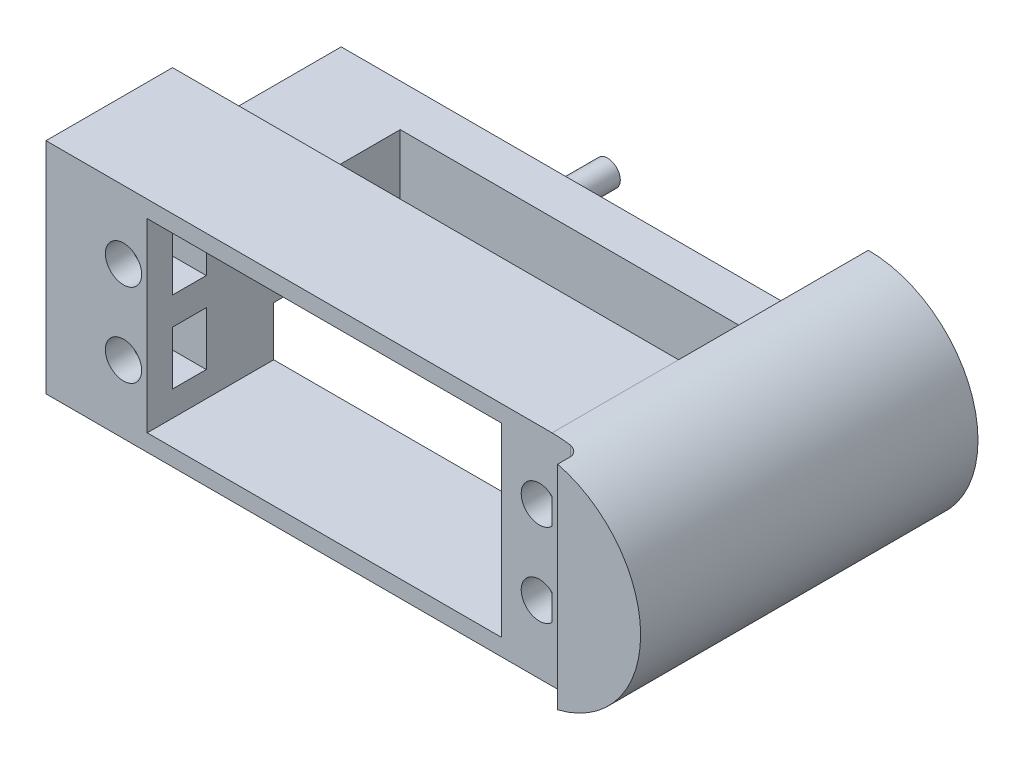
SolidWorks part; units mm, degrees
ref_plane "Plan de face" through (0, 0, 0) normal (0, 0, 1) x (1, 0, 0)
ref_plane "Plan de dessus" through (0, 0, 0) normal (0, 1, 0) x (1, 0, 0)
ref_plane "Plan de droite" through (0, 0, 0) normal (1, 0, 0) x (0, 0, -1)
sketch "Esquisse1" plane through (0, 0, 0) normal (0, 0, 1) x (1, 0, 0)
  line L1 (30, -13) -> (-30, -13)
  line L3 (30, 13) -> (-30, 13)
  line L4 (-30, -13) -> (-30, 13)
  line L5 (30, -13) -> (-30, 13) construction
  line L6 (30, 13) -> (-30, -13) construction
  arc A0 (30, -13) -> (30, 13) centre (30, 0) ccw
  point P0 (0, 0)
  dimension "D1" = 60
  dimension "D2" = 26
extrude "Boss.-Extru.1" add sketch "Esquisse1" along normal blind 15
sketch "Esquisse2" plane through (0, 0, 15) normal (0, 0, 1) x (1, 0, 0)
  line L0 (-30, 13) -> (-30, -13) construction
  line L1 (-18, 11) -> (24, 11)
  line L2 (-18, 11) -> (-18, -11)
  line L3 (-18, -11) -> (24, -11)
  line L4 (24, 11) -> (24, -11)
  point P4 (-18, 0)
  dimension "D1" = 42
  dimension "D2" = 22
  dimension "D3" = 12
extrude "Enlèv. mat.-Extru.1" cut sketch "Esquisse2" against normal through all
sketch "Esquisse4" plane through (0, 0, 15) normal (0, 0, 1) x (1, 0, 0)
  circle A0 centre (-20.81, 4.935) radius 2.15
  circle A1 centre (-20.81, -4.935) radius 2.15
  circle A2 centre (28.49, 4.935) radius 2.15
  circle A3 centre (28.49, -4.935) radius 2.15
extrude "Enlèv. mat.-Extru.2" cut sketch "Esquisse4" against normal blind 3
sketch "Esquisse5" plane through (-18, 0, 0) normal (1, 0, 0) x (0, 0, -1)
  line L1 (-12, -8) -> (-8, -8)
  line L2 (-12, -8) -> (-12, -1.65)
  line L3 (-12, -1.65) -> (-8, -1.65)
  line L4 (-8, -8) -> (-8, -1.65)
  line L5 (-15, 11) -> (-15, -11) construction
  line L6 (0, -11) -> (-15, -11) construction
  line L7 (-16.3207, 0) -> (1.751, 0) construction
  line L8 (-12, 1.65) -> (-8, 1.65)
  line L9 (-8, 8) -> (-8, 1.65)
  line L10 (-12, 8) -> (-8, 8)
  line L11 (-12, 8) -> (-12, 1.65)
  dimension "D1" = 6.35
  dimension "D2" = 4
  dimension "D3" = 3
  dimension "D4" = 3
extrude "Enlèv. mat.-Extru.3" cut sketch "Esquisse5" against normal blind 6
sketch "Esquisse6" plane through (24, 0, 0) normal (-1, 0, 0) x (0, 0, 1)
  line L0 (15, -11) -> (15, 11) construction
  line L1 (12, 8) -> (8, 8)
  line L2 (12, 8) -> (12, 1.65)
  line L3 (12, 1.65) -> (8, 1.65)
  line L4 (8, 8) -> (8, 1.65)
  line L5 (0, 11) -> (15, 11) construction
  line L6 (16.3207, 0) -> (-2.2889, 0) construction
  line L7 (12, -1.65) -> (8, -1.65)
  line L8 (8, -8) -> (8, -1.65)
  line L9 (12, -8) -> (8, -8)
  line L10 (12, -8) -> (12, -1.65)
  dimension "D1" = 6.35
  dimension "D2" = 4
  dimension "D3" = 3
  dimension "D4" = 3
extrude "Enlèv. mat.-Extru.4" cut sketch "Esquisse6" against normal blind 8
sketch "Esquisse10" plane through (0, 0, 0) normal (0, 0, -1) x (-1, 0, 0)
  line L0 (30, 13) -> (30, -13) construction
  line L1 (18, 0) -> (30, 0) construction
  line L2 (18, 11) -> (18, -11) construction
  line L3 (-24, 0) -> (-43, 0) construction
  line L4 (30, -5.1328) -> (18, -5.1328)
  line L5 (30, -5.1328) -> (30, 5.1328)
  line L6 (30, 5.1328) -> (18, 5.1328)
  line L7 (18, -5.1328) -> (18, 5.1328)
  line L8 (30, -5.1328) -> (18, 5.1328) construction
  line L9 (30, 5.1328) -> (18, -5.1328) construction
  line L10 (-24, -11) -> (-24, 11) construction
  line L11 (-24, 5.1328) -> (-41.9438, 5.1328)
  line L12 (-24, -5.1328) -> (-41.9438, -5.1328)
  line L13 (-24, 5.1328) -> (-24, -5.1328)
  arc A0 (-30, 13) -> (-30, -13) centre (-30, 0) ccw construction
  arc A1 (-41.9438, 5.1328) -> (-41.9438, -5.1328) centre (-30, 0) ccw
  point P9 (24, 0)
extrude "Boss.-Extru.6" add sketch "Esquisse10" along normal blind 20
sketch "Esquisse11" plane through (0, 0, -20) normal (0, 0, -1) x (-1, 0, 0)
  line L1 (-24, 5.1328) -> (18, 5.1328)
  line L2 (-24, 5.1328) -> (-24, -5.1328)
  line L3 (-24, -5.1328) -> (18, -5.1328)
  line L4 (18, 5.1328) -> (18, -5.1328)
extrude "Boss.-Extru.7" add sketch "Esquisse11" against normal blind 5
sketch "Esquisse12" plane through (0, 0, -20) normal (0, 0, -1) x (-1, 0, 0)
  line L0 (-30, -13) -> (-30, 13)
  arc A0 (-30, 13) -> (-41.9438, 5.1328) centre (-30, 0) ccw construction
  arc A1 (-41.9438, 5.1328) -> (-41.9438, -5.1328) centre (-30, 0) ccw construction
  arc A2 (-41.9438, -5.1328) -> (-30, -13) centre (-30, 0) ccw construction
  arc A3 (-30, 13) -> (-41.9438, 5.1328) centre (-30, 0) ccw
  arc A4 (-41.9438, 5.1328) -> (-41.9438, -5.1328) centre (-30, 0) ccw
  arc A5 (-41.9438, -5.1328) -> (-30, -13) centre (-30, 0) ccw
extrude "Boss.-Extru.8" add sketch "Esquisse12" against normal blind 35 and the other way blind 2.5
sketch "Esquisse13" plane through (0, 0, 15) normal (0, 0, 1) x (1, 0, 0)
  circle A0 centre (36.0309, 4.6665) radius 1.55
  circle A1 centre (36.0309, -5.3335) radius 1.55
  dimension "D1" = 3.1
  dimension "D2" = 3.1
  dimension "D3" = 10
extrude "Enlèv. mat.-Extru.5" cut sketch "Esquisse13" against normal through all
sketch "Esquisse14" plane through (0, 0, 15) normal (0, 0, 1) x (1, 0, 0)
  line L0 (33.1601, 12.6101) -> (33.1601, -12.6101)
  arc A0 (30, -13) -> (30, 13) centre (30, 0) ccw construction
  arc A1 (33.1601, -12.6101) -> (33.1601, 12.6101) centre (30, 0) ccw
extrude "Boss.-Extru.9" add sketch "Esquisse14" along normal blind 2.5
fillet "Congé1" radius 1 1 edges at (33.1601, 0, 15)
sketch "Esquisse15" plane through (0, 0, -20) normal (0, 0, -1) x (-1, 0, 0)
  circle A0 centre (6.41, 0) radius 1.5
  dimension "D1" = 3
extrude "Boss.-Extru.10" add sketch "Esquisse15" along normal blind 8
fillet "Congé2" radius 3.5 1 edges at (-7.91, 0, -20)
